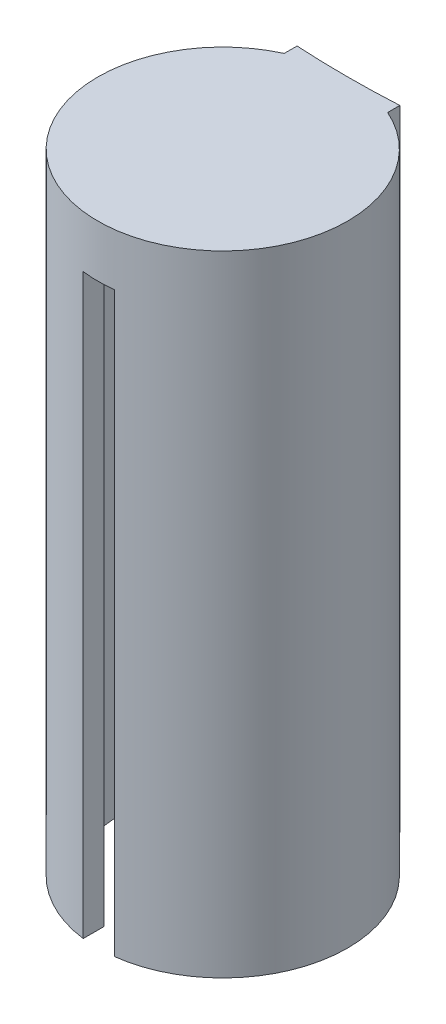
SolidWorks part; units mm, degrees
ref_plane "Front Plane" through (0, 0, 0) normal (0, 0, 1) x (1, 0, 0)
ref_plane "Top Plane" through (0, 0, 0) normal (0, 1, 0) x (1, 0, 0)
ref_plane "Right Plane" through (0, 0, 0) normal (1, 0, 0) x (0, 0, -1)
sketch "Sketch1" plane through (0, 0, 0) normal (0, 1, 0) x (1, 0, 0)
  line L2 (-30, -197.7372) -> (-30, -238.1176)
  line L4 (30, -238.1176) -> (30, -197.7372)
  line L5 (-30, 197.7372) -> (-30, 220)
  line L6 (-30, 220) -> (30, 220)
  line L7 (30, 220) -> (30, 197.7372)
  arc A0 (30, -197.7372) -> (30, 197.7372) centre (0, 0) ccw
  arc A1 (30, -238.1176) -> (-30, -238.1176) centre (0, 0) ccw
  arc A2 (-30, 197.7372) -> (-30, -197.7372) centre (0, 0) ccw
extrude "Boss-Extrude1" add sketch "Sketch1" along normal blind 1110
sketch "Sketch2" plane through (0, 1110, 0) normal (0, 1, 0) x (1, 0, 0)
  circle A0 centre (0, 0) radius 240
extrude "Boss-Extrude2" add sketch "Sketch2" along normal blind 100
sketch "Sketch3" plane through (0, 1210, 0) normal (0, 1, 0) x (1, 0, 0)
  line L1 (-100, 240) -> (-100, 242.8595)
  line L2 (-100, 240) -> (-100, 218.1742)
  line L4 (97.6793, 242.7282) -> (97.6793, 218.1742)
  arc A0 (-100, 242.8595) -> (97.6793, 242.7282) centre (0, 1990) ccw
  circle A1 centre (0, 0) radius 240 construction
  arc A2 (97.6793, 219.2231) -> (-100, 218.1742) centre (0, 0) ccw
  circle M5 centre (0, 0) radius 240
extrude "Boss-Extrude3" add sketch "Sketch3" against normal through all contours A0 L1 L2 M5 | A0 L4 M5
